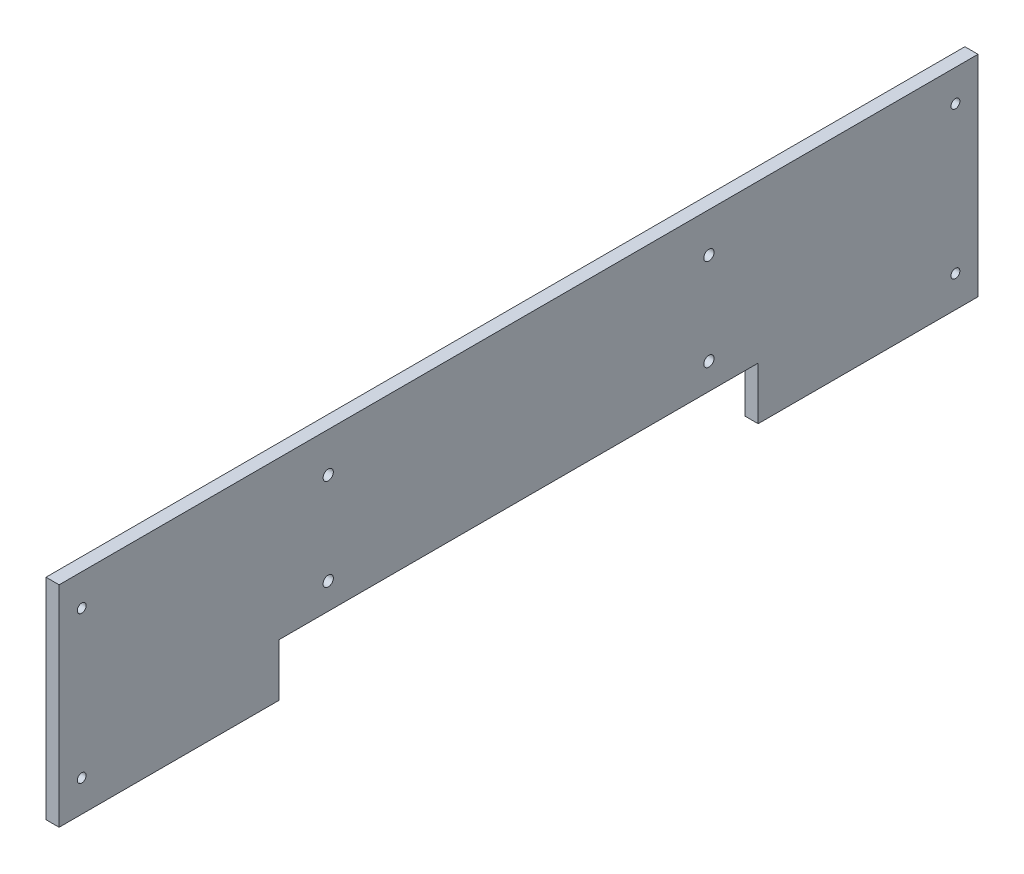
SolidWorks part; units mm, degrees
material "6061-T6 (SS)"
ref_plane "Front Plane" through (0, 0, 0) normal (0, 0, 1) x (1, 0, 0)
ref_plane "Top Plane" through (0, 0, 0) normal (0, 1, 0) x (1, 0, 0)
ref_plane "Right Plane" through (0, 0, 0) normal (1, 0, 0) x (0, 0, -1)
sketch "Sketch1" plane through (0, 0, 0) normal (1, 0, 0) x (0, 0, -1)
  line L1 (-222.25, 50.8) -> (222.25, 50.8)
  line L2 (-222.25, 50.8) -> (-222.25, -50.8)
  line L3 (-222.25, -50.8) -> (222.25, -50.8)
  line L4 (222.25, 50.8) -> (222.25, -50.8)
  line L5 (-222.25, 50.8) -> (222.25, -50.8) construction
  line L6 (-222.25, -50.8) -> (222.25, 50.8) construction
  point P0 (0, 0)
  dimension "D1" = 101.6
  dimension "D2" = 444.5
extrude "Boss-Extrude1" add sketch "Sketch1" along normal blind 6.35
sketch "Sketch2" plane through (6.35, 0, 0) normal (1, 0, 0) x (0, 0, -1)
  line L0 (222.25, -50.8) -> (222.25, 50.8) construction
  line L1 (-188.722, 10.16) -> (211.328, 10.16) construction
  line L2 (-188.722, 10.16) -> (-188.722, -44.45) construction
  line L3 (-188.722, -44.45) -> (211.328, -44.45) construction
  line L4 (211.328, 10.16) -> (211.328, -44.45) construction
  line L5 (-188.722, 10.16) -> (211.328, -44.45) construction
  line L6 (-188.722, -44.45) -> (211.328, 10.16) construction
  line L7 (-222.25, 50.8) -> (-222.25, -50.8) construction
  line L8 (-222.25, -50.8) -> (222.25, -50.8) construction
  line L9 (-222.25, -50.8) -> (222.25, -50.8) construction
  line L10 (222.25, -50.8) -> (222.25, 50.8) construction
  line L11 (130.175, 3.81) -> (47.625, 3.81) construction
  line L12 (130.175, 3.81) -> (130.175, -40.64) construction
  line L13 (130.175, -40.64) -> (47.625, -40.64) construction
  line L14 (47.625, 3.81) -> (47.625, -40.64) construction
  line L15 (130.175, 3.81) -> (47.625, -40.64) construction
  line L16 (130.175, -40.64) -> (47.625, 3.81) construction
  line L17 (-217.4875, 46.9519) -> (-217.4875, 38.7731) construction
  line L18 (-222.25, 50.8) -> (-222.25, -50.8) construction
  line L19 (222.25, 50.8) -> (-222.25, 50.8) construction
  point P0 (11.303, -17.145)
  point P7 (0, 0)
  point P8 (-208.534, -15.24)
  point P14 (-217.4875, 42.8625)
  point P18 (88.9, -18.415)
  dimension "D1" = 10.922
  dimension "D2" = 33.528
  dimension "D3" = 54.61
  dimension "D4" = 13.716
  dimension "D5" = 35.56
  dimension "D6" = 6.35
  dimension "D7" = 82.55
  dimension "D8" = 44.45
  dimension "D9" = 10.16
  dimension "D10" = 92.075
  dimension "D11" = 8.1788
  dimension "D12" = 4.7625
  dimension "D13" = 7.9375
hole_wizard "#10 Clearance Hole1" positions "Sketch3" profile "Sketch4" hole size "#10" standard "ANSI Inch" end condition through all
sketch "Sketch3" plane through (6.35, 0, 0) normal (1, 0, 0) x (0, 0, -1)
  line L0 (222.25, 50.8) -> (-222.25, 50.8) construction
  line L1 (222.25, -50.8) -> (222.25, 50.8) construction
  line L2 (-222.25, 50.8) -> (-222.25, -50.8) construction
  point P28 (92.075, 31.75)
  point P30 (92.075, -12.7)
  point P35 (-92.075, 31.75)
  point P37 (-92.075, -12.7)
  dimension "D1" = 19.05
  dimension "D2" = 44.45
  dimension "D3" = 19.05
  dimension "D4" = 44.45
  dimension "D5" = 130.175
  dimension "D6" = 130.175
  dimension "D7" = 130.175
  dimension "D8" = 130.175
sketch "Sketch4" plane through (6.35, 31.75, -92.075) normal (0, 1, 0) x (0, 0, -1)
  line L0 (0, 0) -> (0, 6.35)
  line L1 (0, 6.35) -> (2.4892, 6.35)
  line L2 (2.4892, 6.35) -> (2.4892, 0)
  line L5 (2.4892, 0) -> (0, 0)
  line L11 (0, -6.35) -> (0, 107.95) construction
  dimension "Thru Hole Dia." = 4.9784
  dimension "Thru Hole Depth" = 6.35
hole_wizard "#8 Clearance Hole1" positions "Sketch7" profile "Sketch8" hole size "#8" standard "ANSI Inch" end condition through all
sketch "Sketch7" plane through (6.35, 0, 0) normal (1, 0, 0) x (0, 0, -1)
  line L0 (-222.25, 50.8) -> (-222.25, -50.8) construction
  line L1 (222.25, 50.8) -> (-222.25, 50.8) construction
  line L2 (222.25, -50.8) -> (222.25, 50.8) construction
  point P24 (-211.328, 35.56)
  point P26 (-211.328, -35.56)
  point P28 (211.328, -35.56)
  point P30 (211.328, 35.56)
  dimension "D1" = 10.922
  dimension "D2" = 10.922
  dimension "D3" = 15.24
  dimension "D4" = 86.36
  dimension "D5" = 10.922
  dimension "D6" = 10.922
  dimension "D7" = 86.36
  dimension "D8" = 15.24
sketch "Sketch8" plane through (6.35, 35.56, 211.328) normal (0, 1, 0) x (0, 0, -1)
  line L0 (0, 0) -> (0, 6.35)
  line L1 (0, 6.35) -> (2.1526, 6.35)
  line L2 (2.1526, 6.35) -> (2.1526, 0)
  line L5 (2.1526, 0) -> (0, 0)
  line L11 (0, -6.35) -> (0, 107.95) construction
  dimension "Thru Hole Dia." = 4.3053
  dimension "Thru Hole Depth" = 6.35
sketch "Sketch9" plane through (6.35, 0, 0) normal (1, 0, 0) x (0, 0, -1)
  line L12 (217.424, -45.974) -> (217.424, 45.974)
  line L13 (217.424, 45.974) -> (-217.424, 45.974)
  line L14 (-217.424, -45.974) -> (217.424, -45.974)
  line L15 (-217.424, 45.974) -> (-217.424, -45.974)
  line L16 (217.424, -45.974) -> (217.424, 45.974)
  line L17 (217.424, 45.974) -> (-217.424, 45.974)
  line L18 (-217.424, -45.974) -> (217.424, -45.974)
  line L19 (-217.424, 45.974) -> (-217.424, -45.974)
  circle A9 centre (-211.328, 35.56) radius 6.35
  circle A10 centre (-211.328, -35.56) radius 6.35
  circle A11 centre (-92.075, 31.75) radius 6.35
  circle A12 centre (-92.075, -12.7) radius 6.35
  circle A13 centre (92.075, 31.75) radius 6.35
  circle A14 centre (92.075, -12.7) radius 6.35
  circle A15 centre (211.328, 35.56) radius 6.35
  circle A16 centre (211.328, -35.56) radius 6.35
  dimension "D3" = 4.826
extrude "Cut-Extrude1" [suppressed] cut sketch "Sketch9" against normal through all
sketch "Sketch11" [suppressed] plane through (0, 0, 0) normal (-1, 0, 0) x (0, 0, 1)
  line L0 (-217.424, -29.972) -> (-217.424, 21.082) construction
  line L1 (-134.8644, -33.274) -> (-205.1636, -33.274) construction
  text T0 "LORD OF THE RINKS" font "Agency FB" height 45.72
  dimension "D1" = 4.064
  dimension "D2" = 10.668
extrude "Boss-Extrude3" [suppressed] add sketch "Sketch11" against normal up to surface (6.35 mm away)
sketch "Sketch12" plane through (6.35, 0, 0) normal (1, 0, 0) x (0, 0, -1)
  line L0 (-222.25, -50.8) -> (222.25, -50.8) construction
  line L1 (-115.8875, -50.8) -> (115.8875, -50.8)
  line L2 (-115.8875, -50.8) -> (-115.8875, -25.4)
  line L3 (-115.8875, -25.4) -> (115.8875, -25.4)
  line L4 (115.8875, -50.8) -> (115.8875, -25.4)
  line L5 (222.25, -50.8) -> (222.25, 50.8) construction
  dimension "D1" = 25.4
  dimension "D2" = 106.3625
  dimension "D3" = 106.3625
extrude "Cut-Extrude2" cut sketch "Sketch12" against normal through all
